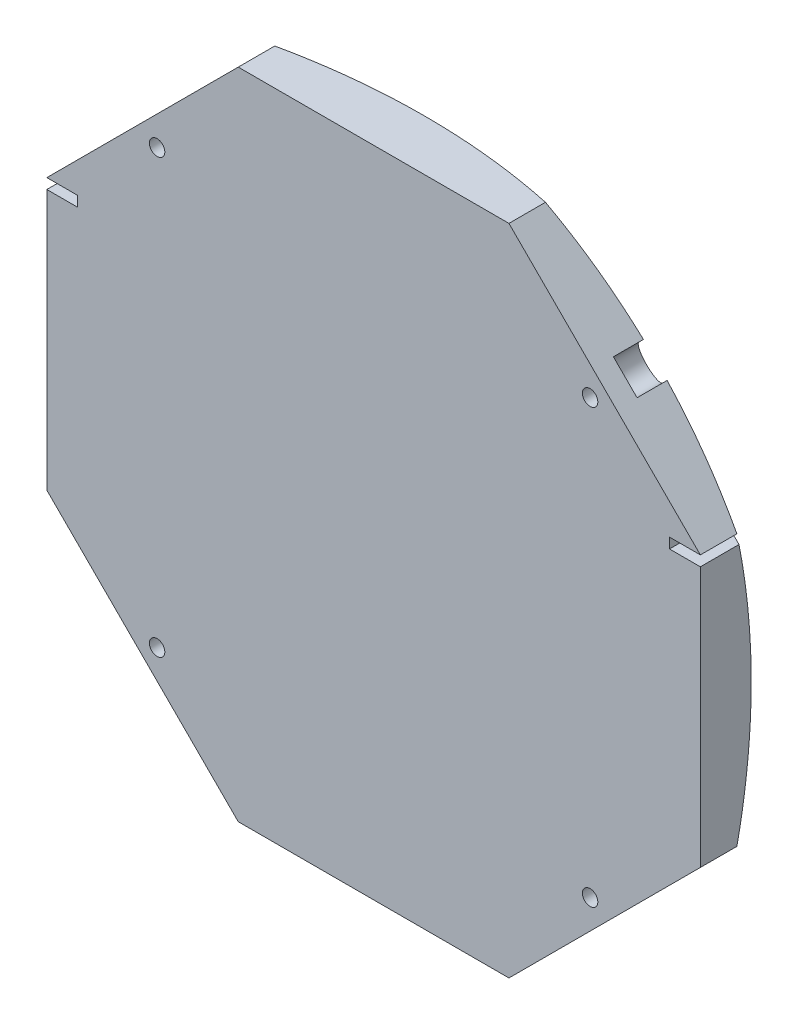
SolidWorks part; units mm, degrees
ref_plane "Plano frontal" through (0, 0, 0) normal (0, 0, 1) x (1, 0, 0)
ref_plane "Plano superior" through (0, 0, 0) normal (0, 1, 0) x (1, 0, 0)
ref_plane "Plano direito" through (0, 0, 0) normal (1, 0, 0) x (0, 0, -1)
sketch "Esboço1" plane through (0, 0, 0) normal (0, 0, 1) x (1, 0, 0)
  line L1 (63.5, 26.3026) -> (26.3026, 63.5)
  line L2 (26.3026, 63.5) -> (-26.3026, 63.5)
  line L3 (-26.3026, 63.5) -> (-63.5, 26.3026)
  line L4 (-63.5, 26.3026) -> (-63.5, -26.3026)
  line L5 (-63.5, -26.3026) -> (-26.3026, -63.5)
  line L6 (-26.3026, -63.5) -> (26.3026, -63.5)
  line L7 (26.3026, -63.5) -> (63.5, -26.3026)
  line L8 (63.5, -26.3026) -> (63.5, 26.3026)
  circle A1 centre (0, 0) radius 63.5 construction
  dimension "D1" = 127
sketch "Esboço2" plane through (0, 0, 0) normal (1, 0, 0) x (0, 0, -1)
  line L0 (0, 74) -> (4, 74)
  line L3 (0, 0) -> (25, 0)
  line L4 (0, 74) -> (0, 0)
  line L5 (25, 0) -> (25, -32.2511) construction
  line L6 (0, 74) -> (0, -63.5) construction
  arc A0 (4, 74) -> (25, 0) centre (-115.881, 0) cw
  dimension "D3" = 74
  dimension "D1" = 4
  dimension "D2" = 25
revolve "Revolução1" add sketch "Esboço2" angle 360 about L3
extrude "Corte-extrusão1" cut sketch "Esboço1" against normal through all flip side to cut
sketch "Esboço3" plane through (0, 0, 0) normal (0, 0, 1) x (1, 0, 0)
  line L1 (-35, 35) -> (35, 35)
  line L2 (-35, 35) -> (-35, -35)
  line L3 (-35, -35) -> (35, -35)
  line L4 (35, 35) -> (35, -35)
  line L5 (-35, 35) -> (35, -35) construction
  line L6 (-35, -35) -> (35, 35) construction
  point P0 (0, 0)
  dimension "D1" = 70
extrude "Corte-extrusão2" cut sketch "Esboço3" against normal through all from offset 4 offset against normal yes
fillet "Filete1" radius 15 4 edges at (35, -35, -10.0092) (-35, -35, -10.0092) (35, 35, -10.0092) (-35, 35, -10.0092)
sketch "Esboço4" plane through (0, 0, -4) normal (0, 0, 1) x (1, 0, 0)
  line L0 (-63.5, 26.3026) -> (-63.5, -26.3026) construction
  line L1 (63.5, 26.3026) -> (-63.5, 26.3026)
  line L2 (63.5, 26.3026) -> (63.5, 24.3026)
  line L3 (63.5, 24.3026) -> (-63.5, 24.3026)
  line L4 (-63.5, 26.3026) -> (-63.5, 24.3026)
  dimension "D1" = 2
extrude "Corte-extrusão4" cut sketch "Esboço4" against normal through all
sketch "Esboço5" plane through (0, 0, -4) normal (0, 0, -1) x (-1, 0, 0)
  line L2 (-57.5, 26.3026) -> (-57.5, 24.3026)
  line L4 (57.5, 26.3026) -> (57.5, 24.3026)
  line L12 (-35, 20) -> (-35, -20)
  line L13 (-33.6117, 26.3026) -> (-63.5, 26.3026)
  line L14 (-63.5, 26.3026) -> (-63.5, 24.3026)
  line L15 (-63.5, 24.3026) -> (-34.3697, 24.3026)
  line L17 (-20, -35) -> (20, -35)
  line L18 (35, -20) -> (35, 20)
  line L19 (34.3697, 24.3026) -> (63.5, 24.3026)
  line L20 (63.5, 24.3026) -> (63.5, 26.3026)
  line L21 (63.5, 26.3026) -> (33.6117, 26.3026)
  line L23 (20, 35) -> (-20, 35)
  line L25 (-57.5, 26.3026) -> (-63.5, 26.3026)
  line L26 (-63.5, 26.3026) -> (-63.5, 24.3026)
  line L27 (-63.5, 24.3026) -> (-57.5, 24.3026)
  line L32 (63.5, 24.3026) -> (63.5, 26.3026)
  line L33 (63.5, 26.3026) -> (57.5, 26.3026)
  line L36 (57.5, 24.3026) -> (63.5, 24.3026)
  arc A2 (-35, -20) -> (-20, -35) centre (-20, -20) ccw
  arc A3 (20, -35) -> (35, -20) centre (20, -20) ccw
  arc A8 (-20, 35) -> (-33.6117, 26.3026) centre (-20, 20) ccw
  arc A10 (-34.3697, 24.3026) -> (-35, 20) centre (-20, 20) ccw
  arc A12 (35, 20) -> (34.3697, 24.3026) centre (20, 20) ccw
  arc A14 (33.6117, 26.3026) -> (20, 35) centre (20, 20) ccw
  dimension "D1" = 0
extrude "Corte-extrusão5" cut sketch "Esboço5" against normal through all
sketch "Esboço6" plane through (0, 0, 0) normal (0, 0, 1) x (1, 0, 0)
  line L3 (42.0729, -42.0729) -> (0, 0) construction
  circle A0 centre (42.0729, -42.0729) radius 1.5
  circle A1 centre (-42.0729, -42.0729) radius 1.5
  circle A2 centre (-42.0729, 42.0729) radius 1.5
  circle A3 centre (42.0729, 42.0729) radius 1.5
  point P13 (0, 0)
  dimension "D1" = 59.5
  dimension "D2" = 3
  dimension "D3" = 4
extrude "Corte-extrusão7" cut sketch "Esboço6" against normal through all
sketch "Esboço7" plane through (0, 0, 0) normal (0, 0, 1) x (1, 0, 0)
  line L0 (42.6032, 47.1994) -> (39.7748, 44.371)
  line L1 (-26.3026, 63.5) -> (-63.5, 26.3026) construction
  line L2 (-47.1994, 42.6032) -> (-44.371, 39.7748)
  line L3 (-42.6032, 47.1994) -> (-39.7748, 44.371)
  line L4 (-42.6032, 47.1994) -> (-47.1994, 42.6032)
  line L5 (47.1994, 42.6032) -> (44.371, 39.7748)
  line L6 (47.1994, 42.6032) -> (42.6032, 47.1994)
  line L7 (47.1994, -42.6032) -> (44.371, -39.7748)
  line L8 (42.6032, -47.1994) -> (39.7748, -44.371)
  line L9 (42.6032, -47.1994) -> (47.1994, -42.6032)
  line L10 (-42.6032, -47.1994) -> (-39.7748, -44.371)
  line L11 (-47.1994, -42.6032) -> (-44.371, -39.7748)
  line L12 (-47.1994, -42.6032) -> (-42.6032, -47.1994)
  arc A0 (-44.371, 39.7748) -> (-39.7748, 44.371) centre (-42.0729, 42.0729) ccw
  arc A1 (39.7748, 44.371) -> (44.371, 39.7748) centre (42.0729, 42.0729) ccw
  arc A2 (44.371, -39.7748) -> (39.7748, -44.371) centre (42.0729, -42.0729) ccw
  arc A3 (-39.7748, -44.371) -> (-44.371, -39.7748) centre (-42.0729, -42.0729) ccw
  point P27 (0, 0)
extrude "Corte-extrusão8" cut sketch "Esboço7" against normal through all from offset 4
